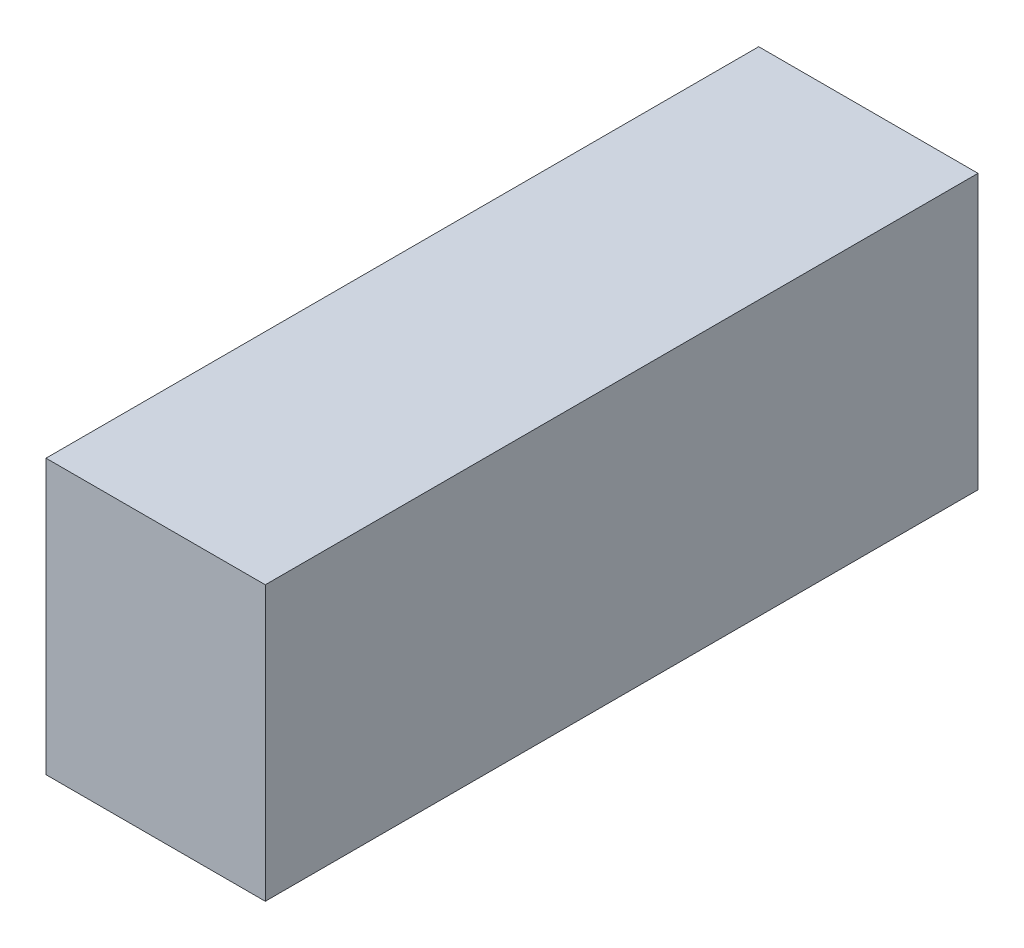
SolidWorks part; units mm, degrees
ref_plane "Front Plane" through (0, 0, 0) normal (0, 0, 1) x (1, 0, 0)
ref_plane "Top Plane" through (0, 0, 0) normal (0, 1, 0) x (1, 0, 0)
ref_plane "Right Plane" through (0, 0, 0) normal (1, 0, 0) x (0, 0, -1)
sketch "Sketch1" plane through (0, 0, 0) normal (0, 0, 1) x (1, 0, 0)
  line L1 (-16.0437, 16.0566) -> (19.5163, 16.0566)
  line L2 (-16.0437, 16.0566) -> (-16.0437, -28.3934)
  line L3 (-16.0437, -28.3934) -> (19.5163, -28.3934)
  line L4 (19.5163, 16.0566) -> (19.5163, -28.3934)
  dimension "D1" = 35.56
  dimension "D2" = 44.45
extrude "Boss-Extrude1" add sketch "Sketch1" along normal blind 115.57
